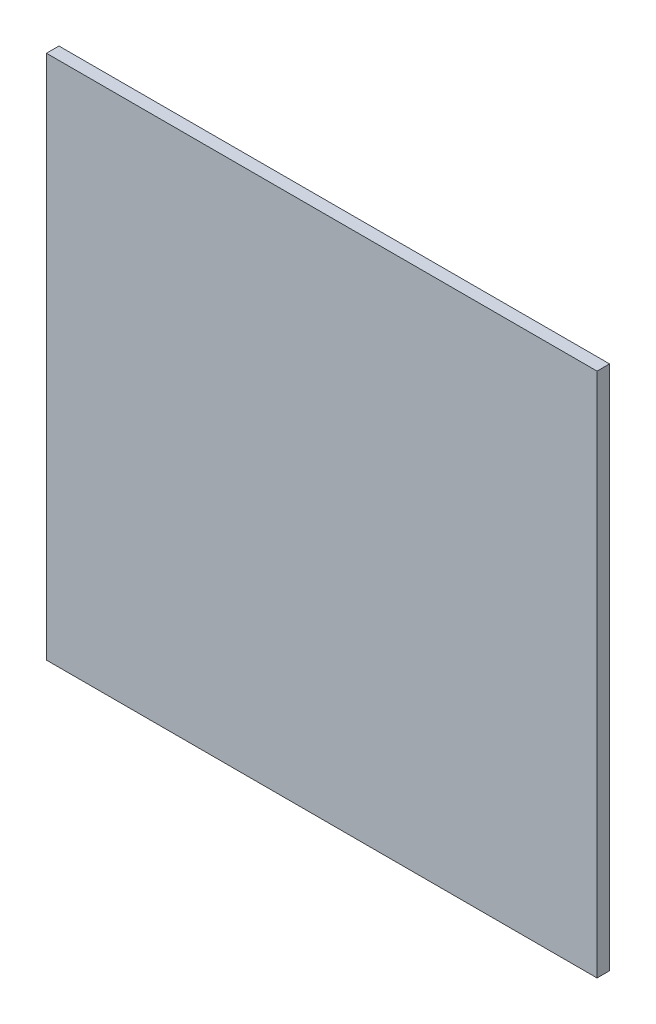
SolidWorks part; units mm, degrees
ref_plane "Plan de face" through (0, 0, 0) normal (0, 0, 1) x (1, 0, 0)
ref_plane "Plan de dessus" through (0, 0, 0) normal (0, 1, 0) x (1, 0, 0)
ref_plane "Plan de droite" through (0, 0, 0) normal (1, 0, 0) x (0, 0, -1)
sketch "Esquisse1" plane through (0, 0, 0) normal (0, 0, 1) x (1, 0, 0)
  line L1 (22, -21) -> (-22, -21)
  line L2 (22, -21) -> (22, 21)
  line L3 (22, 21) -> (-22, 21)
  line L4 (-22, -21) -> (-22, 21)
  line L5 (22, -21) -> (-22, 21) construction
  line L6 (22, 21) -> (-22, -21) construction
  point P0 (0, 0)
  dimension "D1" = 42
  dimension "D2" = 44
extrude "Boss.-Extru.1" add sketch "Esquisse1" along normal blind 1
